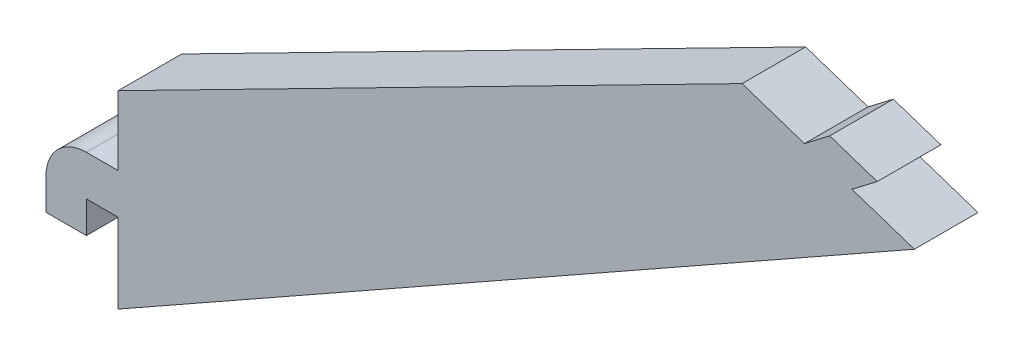
SolidWorks part; units mm, degrees
material "6061 Alloy"
ref_plane "Front Plane" through (0, 0, 0) normal (0, 0, 1) x (1, 0, 0)
ref_plane "Top Plane" through (0, 0, 0) normal (0, 1, 0) x (1, 0, 0)
ref_plane "Right Plane" through (0, 0, 0) normal (1, 0, 0) x (0, 0, -1)
sketch "Sketch2" plane through (0, 0, 0) normal (0, 0, 1) x (1, 0, 0)
  line L2 (-0.1499, 38.5409) -> (6.0809, 36.4693)
  line L3 (6.0809, 36.4693) -> (8.6023, 38.3989)
  line L4 (8.6023, 38.3989) -> (13.3469, 36.8214)
  line L5 (13.3469, 36.8214) -> (10.8256, 34.8918)
  line L6 (10.8256, 34.8918) -> (17.0564, 32.8202)
  line L7 (-62.4477, 6.7809) -> (-62.4477, -0.1311)
  line L11 (-62.4477, -4.1634) -> (-62.4477, -12.1077)
  line L12 (-0.1499, 38.5409) -> (-62.4477, 6.7809)
  line L13 (-62.4477, -12.1077) -> (17.0564, 32.8202)
  line L19 (-69.655, -7.3384) -> (-69.655, -4.1634)
  line L20 (-65.6227, -7.3384) -> (-69.655, -7.3384)
  line L21 (-65.6227, -4.1634) -> (-65.6227, -7.3384)
  line L22 (-65.6227, -0.1311) -> (-62.4477, -0.1311)
  line L23 (-62.4477, -4.1634) -> (-65.6227, -4.1634)
  arc A1 (-69.655, -4.1634) -> (-65.6227, -0.1311) centre (-65.6227, -4.1634) cw
extrude "Boss-Extrude1" add sketch "Sketch2" along normal blind 6.35
sketch "Sketch3" plane through (0, 0, 6.35) normal (0, 0, 1) x (1, 0, 0)
  line L12 (-62.4477, -4.1634) -> (-62.4477, -12.1077)
  line L13 (-62.4477, -12.1077) -> (17.0564, 32.8202)
  line L14 (17.0564, 32.8202) -> (10.8256, 34.8918)
  line L15 (10.8256, 34.8918) -> (13.3469, 36.8214)
  line L16 (13.3469, 36.8214) -> (8.6023, 38.3989)
  line L17 (8.6023, 38.3989) -> (6.0809, 36.4693)
  line L18 (6.0809, 36.4693) -> (-0.1499, 38.5409)
  line L19 (-0.1499, 38.5409) -> (-62.4477, 6.7809)
  line L20 (-62.4477, 6.7809) -> (-62.4477, -0.1311)
  line L21 (-69.655, -4.1634) -> (-69.655, -7.3384)
  line L22 (-69.655, -4.1634) -> (-69.655, -7.3384)
  line L23 (-69.655, -7.3384) -> (-65.6227, -7.3384)
  line L24 (-62.4477, -4.1634) -> (-62.4477, -12.1077)
  line L25 (-62.4477, -12.1077) -> (17.0564, 32.8202)
  line L26 (17.0564, 32.8202) -> (10.8256, 34.8918)
  line L27 (10.8256, 34.8918) -> (13.3469, 36.8214)
  line L28 (13.3469, 36.8214) -> (8.6023, 38.3989)
  line L29 (8.6023, 38.3989) -> (6.0809, 36.4693)
  line L30 (6.0809, 36.4693) -> (-0.1499, 38.5409)
  line L31 (-0.1499, 38.5409) -> (-62.4477, 6.7809)
  line L32 (-62.4477, 6.7809) -> (-62.4477, -0.1311)
  line L38 (-69.655, -7.3384) -> (-65.6227, -7.3384)
  line L39 (-65.6227, -7.3384) -> (-65.6227, -4.1634)
  line L40 (-65.6227, -7.3384) -> (-65.6227, -4.1634)
  line L41 (-65.6227, -4.1634) -> (-62.4477, -4.1634)
  line L42 (-65.6227, -4.1634) -> (-62.4477, -4.1634)
  line L43 (-62.4477, -0.1311) -> (-65.6227, -0.1311)
  line L44 (-62.4477, -0.1311) -> (-65.6227, -0.1311)
  arc A1 (-65.6227, -0.1311) -> (-69.655, -4.1634) centre (-65.6227, -4.1634) ccw
  arc A2 (-65.6227, -0.1311) -> (-69.655, -4.1634) centre (-65.6227, -4.1634) ccw
  dimension "D1" = 0
